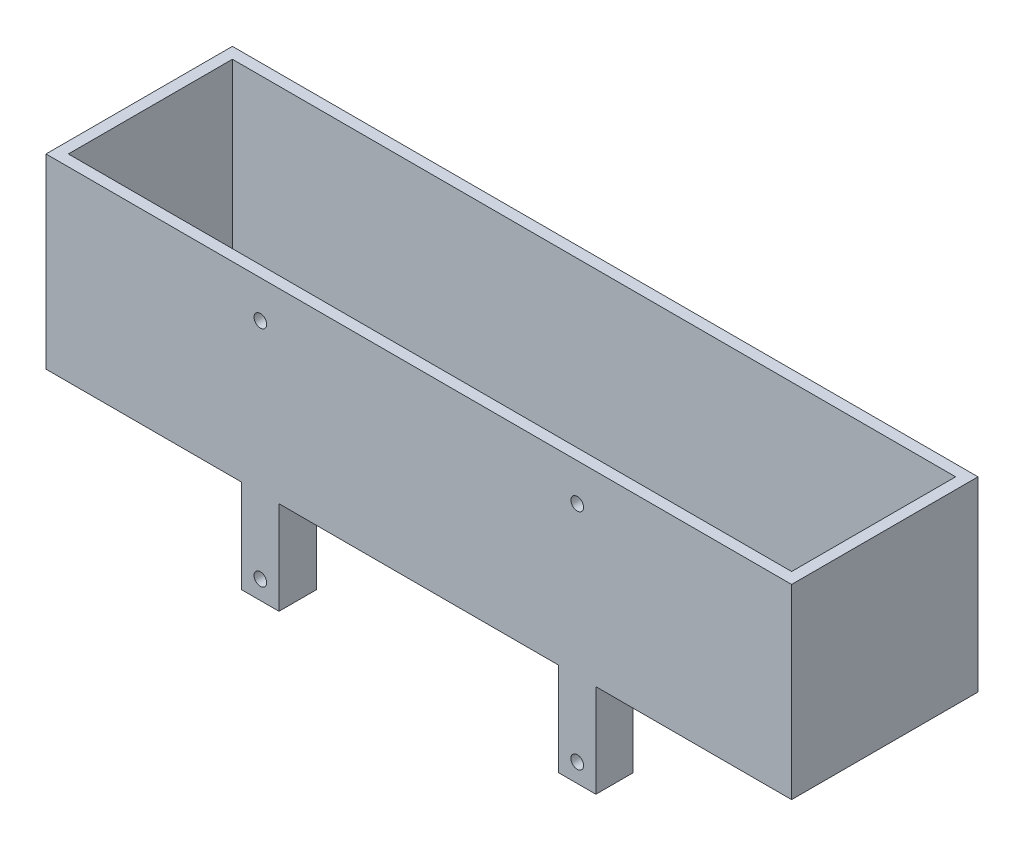
SolidWorks part; units mm, degrees
ref_plane "前视基准面" through (0, 0, 0) normal (0, 0, 1) x (1, 0, 0)
ref_plane "上视基准面" through (0, 0, 0) normal (0, 1, 0) x (1, 0, 0)
ref_plane "右视基准面" through (0, 0, 0) normal (1, 0, 0) x (0, 0, -1)
other "Configuration Table"
sketch "Box footprint 200 x 50 mm" plane through (0, 0, 0) normal (0, 0, 1) x (1, 0, 0)
  line L1 (-100, 0) -> (100, 0)
  line L2 (-100, 0) -> (-100, 50)
  line L3 (-100, 50) -> (100, 50)
  line L4 (100, 0) -> (100, 50)
extrude "Box height 50 mm" add sketch "Box footprint 200 x 50 mm" along normal blind 50
sketch "Rear opening 194 x 44 mm" plane through (0, 50, 0) normal (0, 1, 0) x (1, 0, 0)
  line L1 (-97, -3) -> (97, -3)
  line L2 (-97, -3) -> (-97, -47)
  line L3 (-97, -47) -> (97, -47)
  line L4 (97, -3) -> (97, -47)
extrude "Rear cavity - wall 3 mm" cut sketch "Rear opening 194 x 44 mm" against normal blind 47
sketch "Two square arms 10 x 10 - pitch 85 mm" plane through (0, 0, 0) normal (0, -1, 0) x (1, 0, 0)
  line L1 (-47.5, 40) -> (-37.5, 40)
  line L2 (-47.5, 40) -> (-47.5, 50)
  line L3 (-47.5, 50) -> (-37.5, 50)
  line L4 (-37.5, 40) -> (-37.5, 50)
  line L6 (37.5, 40) -> (47.5, 40)
  line L7 (37.5, 40) -> (37.5, 50)
  line L8 (37.5, 50) -> (47.5, 50)
  line L9 (47.5, 40) -> (47.5, 50)
extrude "Forward square arms 25 mm" add sketch "Two square arms 10 x 10 - pitch 85 mm" along normal blind 25
sketch "Temporary chassis holes - 140 x 20 mm" plane through (0, 0, 0) normal (0, -1, 0) x (1, 0, 0)
  circle A0 centre (-70, 15) radius 1.7
  circle A1 centre (-70, 35) radius 1.7
  circle A2 centre (70, 15) radius 1.7
  circle A3 centre (70, 35) radius 1.7
extrude "4x M3 clearance diameter 3.4 mm" cut sketch "Temporary chassis holes - 140 x 20 mm" against normal blind 3
sketch "PCB rear pair - pitch 85 mm" plane through (0, 0, 50) normal (0, 0, 1) x (1, 0, 0)
  circle A0 centre (-42.5, 40) radius 1.7
  circle A1 centre (42.5, 40) radius 1.7
extrude "2x roof holes diameter 3.4 mm" cut sketch "PCB rear pair - pitch 85 mm" against normal blind 3
sketch "PCB front pair - row spacing 60 mm" plane through (0, 0, 50) normal (0, 0, 1) x (1, 0, 0)
  circle A0 centre (-42.5, -20) radius 1.7
  circle A1 centre (42.5, -20) radius 1.7
extrude "2x arm holes through top and bottom 3.4 mm" cut sketch "PCB front pair - row spacing 60 mm" against normal blind 10
